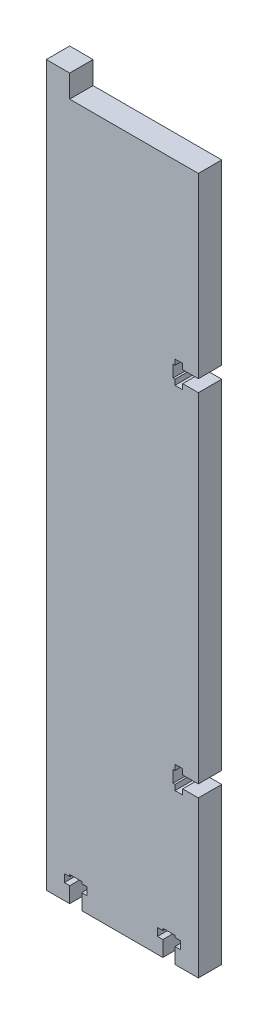
SolidWorks part; units mm, degrees
ref_plane "Płaszczyzna przednia" through (0, 0, 0) normal (0, 0, 1) x (1, 0, 0)
ref_plane "Płaszczyzna górna" through (0, 0, 0) normal (0, 1, 0) x (1, 0, 0)
ref_plane "Płaszczyzna prawa" through (0, 0, 0) normal (1, 0, 0) x (0, 0, -1)
sketch "Szkic1" plane through (0, 0, 0) normal (0, 0, 1) x (1, 0, 0)
  line L0 (-16.4912, -200) -> (-55.4912, -200)
  line L1 (-16.4912, -200) -> (-16.4912, -21.3)
  line L2 (-55.4912, -200) -> (-55.4912, -21.3)
  line L3 (-16.4912, -21.3) -> (-55.4912, -21.3)
  dimension "D1" = 178.7
  dimension "D2" = 39
extrude "Dodanie-wyciągnięcie1" add sketch "Szkic1" against normal blind 6
sketch "Szkic2" plane through (0, 0, -6) normal (0, 0, -1) x (-1, 0, 0)
  line L0 (16.4912, -160) -> (16.4912, -156.9)
  line L1 (16.4912, -160) -> (20.4912, -160)
  line L2 (16.4912, -156.9) -> (20.4912, -156.9)
  line L3 (22.9912, -160) -> (22.9912, -156.9)
  line L4 (16.4912, -200) -> (16.4912, -21.3) construction
  line L5 (22.4912, -161.375) -> (22.4912, -160)
  line L6 (22.4912, -161.375) -> (20.4912, -161.375)
  line L7 (22.4912, -155.525) -> (20.4912, -155.525)
  line L8 (20.4912, -161.375) -> (20.4912, -160)
  line L9 (22.4912, -156.9) -> (22.4912, -155.525)
  line L10 (22.4912, -160) -> (22.9912, -160)
  line L11 (20.4912, -156.9) -> (20.4912, -155.525)
  line L12 (22.4912, -156.9) -> (22.9912, -156.9)
  line L13 (55.4912, -200) -> (16.4912, -200) construction
  dimension "D1" = 6.5
  dimension "D2" = 3.1
  dimension "D3" = 2
  dimension "D4" = 5.85
  dimension "D5" = 1.375
  dimension "D6" = 0.5
  dimension "D7" = 40
extrude "Wytnij-wyciągnięcie1" cut sketch "Szkic2" against normal through all
sketch "Szkic3" plane through (0, 0, -6) normal (0, 0, -1) x (-1, 0, 0)
  line L0 (49.4912, -200) -> (49.4912, -196)
  line L1 (49.4912, -200) -> (46.3912, -200)
  line L2 (49.4912, -193.5) -> (46.3912, -193.5)
  line L3 (46.3912, -200) -> (46.3912, -196)
  line L4 (55.4912, -200) -> (16.4912, -200) construction
  line L5 (50.8662, -196) -> (49.4912, -196)
  line L6 (50.8662, -196) -> (50.8662, -194)
  line L7 (45.0162, -196) -> (45.0162, -194)
  line L8 (50.8662, -194) -> (49.4912, -194)
  line L9 (49.4912, -194) -> (49.4912, -193.5)
  line L10 (46.3912, -194) -> (46.3912, -193.5)
  line L11 (46.3912, -196) -> (45.0162, -196)
  line L12 (46.3912, -194) -> (45.0162, -194)
  line L13 (55.4912, -206) -> (55.4912, -21) construction
  dimension "D1" = 6.5
  dimension "D2" = 2
  dimension "D3" = 5.85
  dimension "D4" = 1.375
  dimension "D5" = 3.1
  dimension "D6" = 0.5
  dimension "D7" = 6
extrude "Wytnij-wyciągnięcie2" cut sketch "Szkic3" against normal through all
pattern_linear "Szyk liniowy1" count 2 spacing 90 along (0, 1, 0) of "Wytnij-wyciągnięcie1"
pattern_linear "Szyk liniowy2" count 2 spacing 23.9 along (1, 0, 0) of "Wytnij-wyciągnięcie2"
sketch "Szkic4" plane through (0, -21.3, 0) normal (0, 1, 0) x (1, 0, 0)
  line L0 (-55.4912, 6) -> (-49.4912, 6)
  line L1 (-55.4912, 6) -> (-55.4912, 0)
  line L2 (-49.4912, 6) -> (-49.4912, 0)
  line L3 (-55.4912, 0) -> (-49.4912, 0)
  line L4 (-16.4912, 6) -> (-55.4912, 6) construction
  dimension "D1" = 6
  dimension "D2" = 6
extrude "Dodanie-wyciągnięcie2" add sketch "Szkic4" along normal blind 5.8
equation "\"tolerancja_wpusy\"=0.2"
equation "\"dlugosc_wpustu_duzy\"=20"
equation "\"srednica_otworu_M3\"=3.1"
equation "\"szerokosc_nogi_T\"=3.1"
equation "\"dlugosc_T_30\"=11"
equation "\"grubosc_na_nakretke_kwadrat\"=2"
equation "\"szerokosc_na_nakretke_kwadrat\"=5.85"
equation "\"wyokosc_nadstawki_T\"=0.5"
equation "\"dlugosc_T_20_6\"=14"
equation "\"D2@Szkic2\"=\"szerokosc_nogi_T\""
equation "\"D3@Szkic2\"=\"grubosc_na_nakretke_kwadrat\""
equation "\"D4@Szkic2\"=\"szerokosc_na_nakretke_kwadrat\""
equation "\"D5@Szkic2\"=(\"szerokosc_na_nakretke_kwadrat\"-\"szerokosc_nogi_T\")/2"
equation "\"D6@Szkic2\"=\"wyokosc_nadstawki_T\""
equation "\"D2@Szkic3\"=\"grubosc_na_nakretke_kwadrat\""
equation "\"D3@Szkic3\"=\"szerokosc_na_nakretke_kwadrat\""
equation "\"D4@Szkic3\"=(\"szerokosc_na_nakretke_kwadrat\"-\"szerokosc_nogi_T\")/2"
equation "\"D5@Szkic3\"=\"szerokosc_nogi_T\""
equation "\"D6@Szkic3\"=\"wyokosc_nadstawki_T\""
